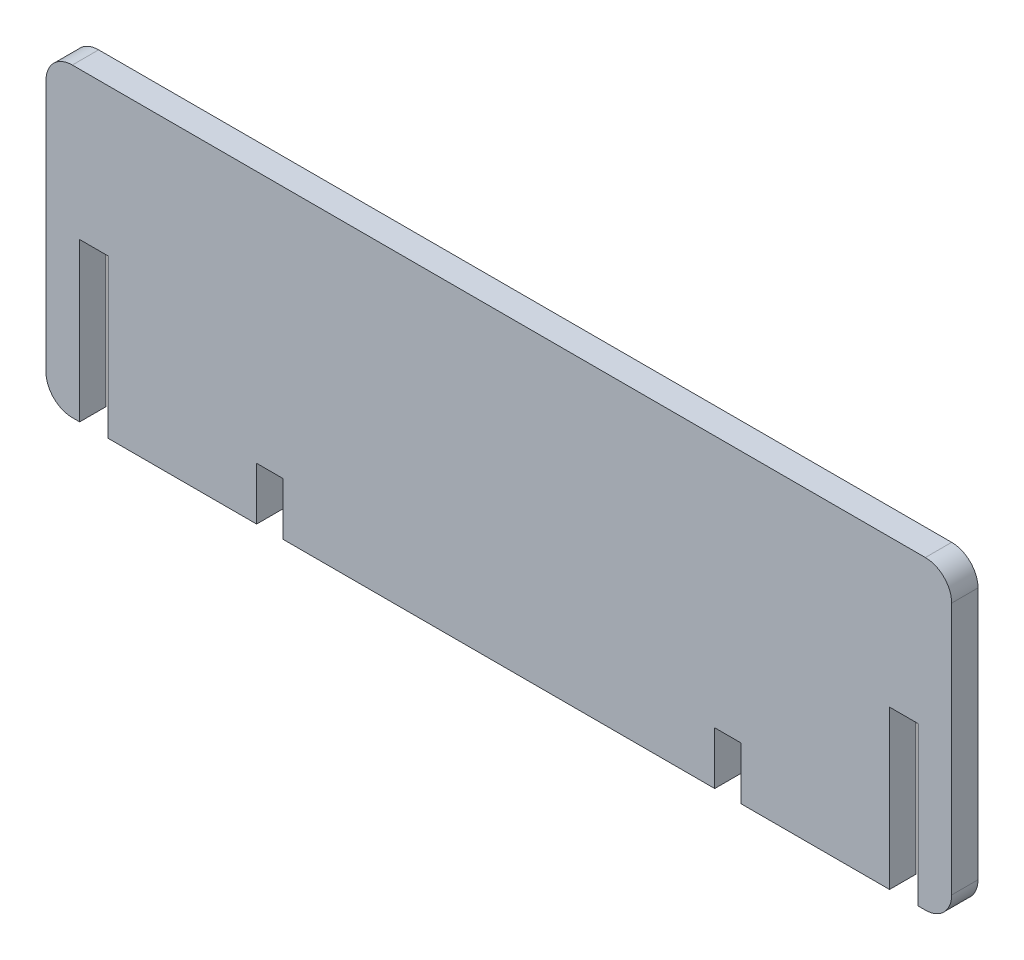
SolidWorks part; units mm, degrees
ref_plane "Plano frontal" through (0, 0, 0) normal (0, 0, 1) x (1, 0, 0)
ref_plane "Plano superior" through (0, 0, 0) normal (0, 1, 0) x (1, 0, 0)
ref_plane "Plano direito" through (0, 0, 0) normal (1, 0, 0) x (0, 0, -1)
sketch "Esboço1" plane through (0, 0, 0) normal (0, 0, 1) x (1, 0, 0)
  line L86 (-27.6312, -72.4055) -> (53.3688, -72.4055)
  line L87 (-30.1312, -74.9055) -> (-30.1312, -98.9055)
  line L88 (-27.6312, -101.4055) -> (53.3688, -101.4055)
  line L89 (55.8688, -74.9055) -> (55.8688, -98.9055)
  line L90 (-26.9343, -86.4055) -> (-24.2312, -86.4055)
  line L91 (-26.9343, -86.4055) -> (-26.9343, -101.4055)
  line L92 (-26.9343, -101.4055) -> (-24.2312, -101.4055)
  line L93 (-24.2312, -86.4055) -> (-24.2312, -101.4055)
  line L94 (-10.1312, -101.4055) -> (-7.6312, -101.4055)
  line L95 (-10.1312, -101.4055) -> (-10.1312, -96.4055)
  line L96 (-10.1312, -96.4055) -> (-7.6312, -96.4055)
  line L97 (-7.6312, -101.4055) -> (-7.6312, -96.4055)
  line L98 (33.3688, -101.4055) -> (35.8688, -101.4055)
  line L99 (33.3688, -101.4055) -> (33.3688, -96.4055)
  line L100 (33.3688, -96.4055) -> (35.8688, -96.4055)
  line L101 (35.8688, -101.4055) -> (35.8688, -96.4055)
  line L102 (49.9688, -101.4055) -> (52.6718, -101.4055)
  line L103 (49.9688, -101.4055) -> (49.9688, -86.4055)
  line L104 (49.9688, -86.4055) -> (52.6718, -86.4055)
  line L105 (52.6718, -101.4055) -> (52.6718, -86.4055)
  arc A20 (-27.6312, -72.4055) -> (-30.1312, -74.9055) centre (-27.6312, -74.9055) ccw
  arc A21 (53.3688, -72.4055) -> (55.8688, -74.9055) centre (53.3688, -74.9055) cw
  arc A22 (53.3688, -101.4055) -> (55.8688, -98.9055) centre (53.3688, -98.9055) ccw
  arc A23 (-30.1312, -98.9055) -> (-27.6312, -101.4055) centre (-27.6312, -98.9055) ccw
  point P174 (12.8688, -101.4055)
  dimension "D49" = 2.5
  dimension "D50" = 74.2
  dimension "D51" = 37.1
  dimension "D52" = 15
  dimension "D53" = 41
  dimension "D54" = 2.5
  dimension "D55" = 5
  dimension "D56" = 20.5
extrude "Ressalto-extrusão1" add sketch "Esboço1" along normal blind 2.5 contours L87 A23 L88 L91 L90 L93 L95 L96 L97 L99 L100 L101 L103 L104 L105 A22 L89 A21 L86 A20
